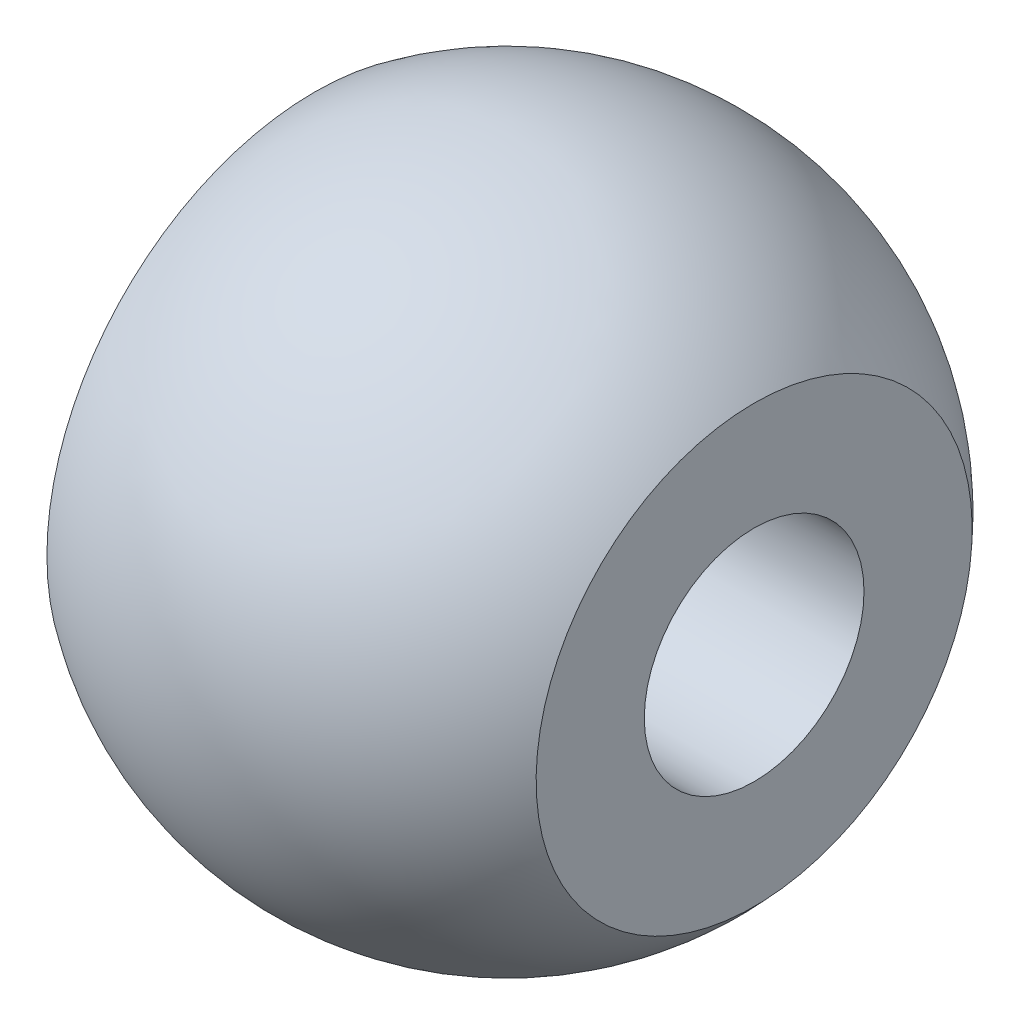
SolidWorks part; units mm, degrees
ref_plane "Front Plane" through (0, 0, 0) normal (0, 0, 1) x (1, 0, 0)
ref_plane "Top Plane" through (0, 0, 0) normal (0, 1, 0) x (1, 0, 0)
ref_plane "Right Plane" through (0, 0, 0) normal (1, 0, 0) x (0, 0, -1)
sketch "Sketch1" plane through (0, 0, 0) normal (0, 0, 1) x (1, 0, 0)
  line L0 (0, 0) -> (0, 50000) construction
  line L1 (0, 0) -> (50000, 0) construction
  line L2 (5.6569, 2) -> (-5.6569, 2)
  line L3 (-1.841, 2) -> (-3.5, 4.8734)
  line L4 (4.5, 3.9686) -> (4.5, 2)
  line L5 (-4.5, 3.9686) -> (-4.5, 2)
  arc A0 (6, 0) -> (-6, 0) centre (0, 0) ccw
  point P16 (0, 0)
  point P17 (0, 0)
  point P18 (0, 0)
  point P19 (0, 0)
  point P20 (3.1323, 3.399)
  point P21 (3.0842, 5.1466)
  dimension "D1" = 12
  dimension "D2" = 9
  dimension "D3" = 1
  dimension "D4" = 60
  dimension "D5" = 4
revolve "Revolve1" add sketch "Sketch1" angle 360 about L1
